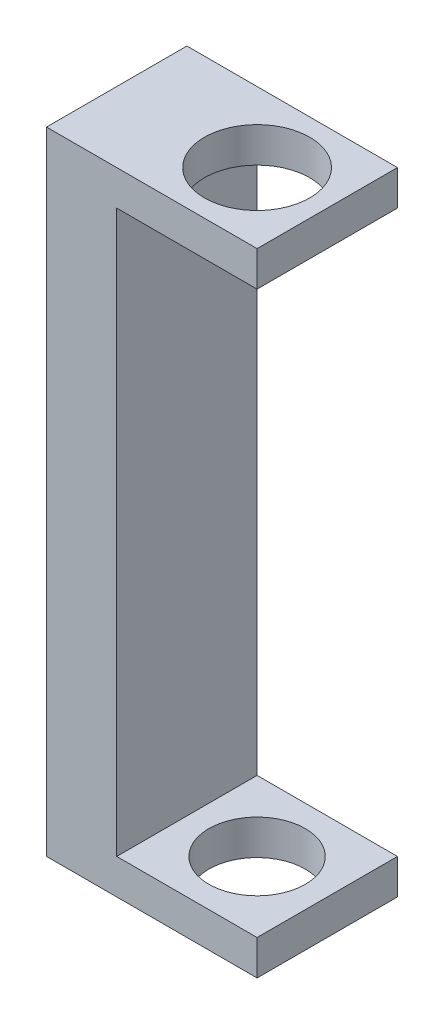
SolidWorks part; units mm, degrees
ref_plane "Front Plane" through (0, 0, 0) normal (0, 0, 1) x (1, 0, 0)
ref_plane "Top Plane" through (0, 0, 0) normal (0, 1, 0) x (1, 0, 0)
ref_plane "Right Plane" through (0, 0, 0) normal (1, 0, 0) x (0, 0, -1)
sketch "Sketch1" plane through (0, 0, 0) normal (0, 1, 0) x (1, 0, 0)
  line L1 (0, 0) -> (76.2, 0)
  line L2 (0, 0) -> (0, 50.8)
  line L3 (0, 50.8) -> (76.2, 50.8)
  line L4 (76.2, 0) -> (76.2, 50.8)
  dimension "D1" = 50.8
  dimension "D2" = 76.2
extrude "Boss-Extrude1" add sketch "Sketch1" along normal blind 228.6
sketch "Sketch2" plane through (0, 0, 0) normal (0, 0, 1) x (1, 0, 0)
  line L0 (76.2, 228.6) -> (76.2, 0) construction
  line L1 (76.2, 215.9) -> (25.4, 215.9)
  line L2 (76.2, 215.9) -> (76.2, 12.7)
  line L3 (76.2, 12.7) -> (25.4, 12.7)
  line L4 (25.4, 215.9) -> (25.4, 12.7)
  line L5 (0, 228.6) -> (76.2, 228.6) construction
  line L6 (0, 0) -> (76.2, 0) construction
  dimension "D1" = 12.7
  dimension "D2" = 12.7
  dimension "D3" = 50.8
extrude "Cut-Extrude1" cut sketch "Sketch2" against normal through all
sketch "Sketch5" plane through (0, 228.6, 0) normal (0, 1, 0) x (1, 0, 0)
  line L0 (25.4, 50.8) -> (25.4, 0) construction
  line L1 (25.4, 50.8) -> (25.4, 0) construction
  line L2 (25.4, 50.8) -> (76.2, 0) construction
  circle A0 centre (50.8, 25.4) radius 19.05
  dimension "D1" = 38.1
extrude "Cut-Extrude2" cut sketch "Sketch5" against normal up to next
sketch "Sketch8" plane through (0, 0, 0) normal (0, -1, 0) x (1, 0, 0)
  line L0 (25.4, -50.8) -> (25.4, 0) construction
  line L1 (25.4, -50.8) -> (25.4, 0) construction
  line L2 (25.4, 0) -> (76.2, -50.8) construction
  circle A0 centre (50.8, -25.4) radius 17.4625
  dimension "D1" = 34.925
extrude "Cut-Extrude3" cut sketch "Sketch8" against normal up to next
hole_wizard "#10-32 Tapped Hole1" positions "Sketch10" profile "Sketch9" tap size "#10-32" standard "ANSI Inch"
sketch "Sketch10" plane through (0, 0, 0) normal (0, -1, 0) x (-1, 0, 0)
  line L0 (-25.4, 50.8) -> (-25.4, 0) construction
  line L1 (-25.4, 50.8) -> (-25.4, 0) construction
  line L3 (-12.7, 50.8) -> (-12.7, 0) construction
  line L4 (-76.2, 50.8) -> (0, 50.8) construction
  line L5 (0, 0) -> (-76.2, 0) construction
  line L7 (-25.4, 25.4) -> (0, 25.4) construction
  line L8 (0, 50.8) -> (0, 0) construction
  point P0 (-6.35, 44.45)
  point P28 (-12.7, 25.4)
  point P33 (-19.05, 44.45)
  point P35 (-6.35, 6.35)
  point P36 (-19.05, 6.35)
  dimension "D1" = 6.35
  dimension "D2" = 6.35
cosmetic thread "Hole Thread1" parameters "D1"=38.1, "D2"=4.826
cosmetic thread "Hole Thread2" parameters "D1"=38.1, "D2"=4.826
cosmetic thread "Hole Thread3" parameters "D1"=38.1, "D2"=4.826
cosmetic thread "Hole Thread4" parameters "D1"=38.1, "D2"=4.826
sketch "Sketch9" plane through (6.35, 0, -44.45) normal (1, 0, 0) x (0, 0, -1)
  line L0 (0, 0) -> (0, 43.2757)
  line L1 (0, 43.2757) -> (2.0193, 42.0624)
  line L2 (2.0193, 42.0624) -> (2.0193, 0)
  line L5 (2.0193, 0) -> (0, 0)
  line L10 (0, 43.2757) -> (-2.0193, 42.0624) construction
  line L11 (0, -6.35) -> (0, 107.95) construction
  dimension "Tap Drill Dia." = 4.0386
  dimension "Tap Drill Depth" = 42.0624
  dimension "Drill Angle" = 118
